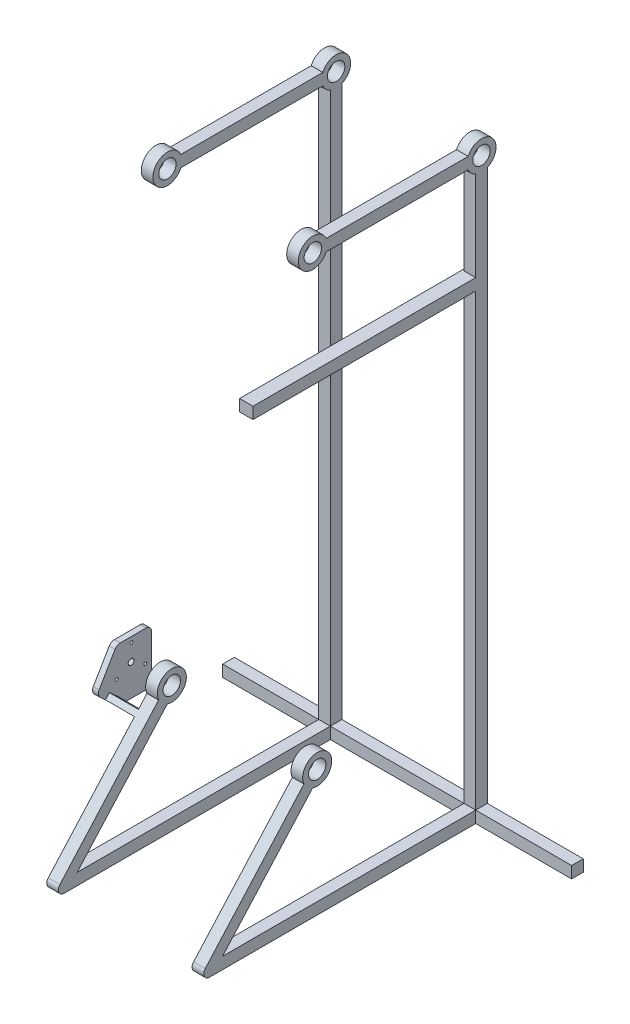
SolidWorks part; units mm, degrees
ref_plane "Front Plane" through (0, 0, 0) normal (0, 0, 1) x (1, 0, 0)
ref_plane "Top Plane" through (0, 0, 0) normal (0, 1, 0) x (1, 0, 0)
ref_plane "Right Plane" through (0, 0, 0) normal (1, 0, 0) x (0, 0, -1)
sketch "Sketch1" plane through (0, 0, 0) normal (1, 0, 0) x (0, 0, -1)
  line L0 (-277.0871, 516.4564) -> (-32.9129, 516.4564)
  line L1 (0, 483.5436) -> (0, -483.5436)
  line L2 (0, -483.5436) -> (-500, -483.5436)
  line L3 (-500, -483.5436) -> (-315.2753, -277.015)
  line L4 (-277.0871, 496.4564) -> (-32.9129, 496.4564)
  line L5 (-20, 483.5436) -> (-20, -463.5436)
  line L6 (-20, -463.5436) -> (-455.2786, -463.5436)
  line L7 (-455.2786, -463.5436) -> (-300.3681, -290.3483)
  line L8 (-300, -259.9368) -> (-285.0929, -273.2701) construction
  line L9 (-20, 496.4564) -> (0, 516.4564) construction
  line L10 (-300, 516.4564) -> (-300, 496.4564) construction
  line L11 (-300, 516.4564) -> (0, 516.4564) construction
  line L12 (-300, 496.4564) -> (-20, 496.4564) construction
  line L13 (-20, 496.4564) -> (-20, -463.5436) construction
  line L14 (0, 516.4564) -> (0, -483.5436) construction
  line L15 (-455.2786, -463.5436) -> (-285.0929, -273.2701) construction
  line L16 (-500, -483.5436) -> (-300, -259.9368) construction
  arc A0 (-32.9129, 496.4564) -> (-20, 483.5436) centre (-10, 506.4564) ccw
  arc A1 (-277.0871, 516.4564) -> (-277.0871, 496.4564) centre (-300, 506.4564) ccw
  arc A2 (-300.3681, -290.3483) -> (-315.2753, -277.015) centre (-292.5464, -266.6034) ccw
  circle A3 centre (-292.5464, -266.6034) radius 15
  circle A4 centre (-300, 506.4564) radius 15
  circle A5 centre (-10, 506.4564) radius 15
  arc A6 (0, 483.5436) -> (-32.9129, 516.4564) centre (-10, 506.4564) ccw
  point P17 (-300, 506.4564)
  point P18 (-292.5464, -266.6034)
  point P20 (-10, 506.4564)
  dimension "D6" = 50
  dimension "D7" = 30
  dimension "D8" = 30
  dimension "D9" = 30
  dimension "D1" = 1000
  dimension "D2" = 300
  dimension "D3" = 300
  dimension "D4" = 500
  dimension "D5" = 20
extrude "Boss-Extrude1" add sketch "Sketch1" along normal blind 20
fillet "Fillet1" radius 10 1 edges at (10, -483.5436, 500)
ref_plane "Plane1" through (-115, 0, 0) normal (1, 0, 0) x (0, 0, -1)
mirror "Mirror2" about plane through (-115, 0, 0) normal (1, 0, 0) of bodies 101
sketch "Sketch2" plane through (-115, 0, 0) normal (1, 0, 0) x (0, 0, -1)
  line L1 (-20, -463.5436) -> (0, -463.5436)
  line L2 (-20, -463.5436) -> (-20, -483.5436)
  line L3 (-20, -483.5436) -> (0, -483.5436)
  line L4 (0, -463.5436) -> (0, -483.5436)
extrude "Boss-Extrude2" add sketch "Sketch2" along normal blind 300 and the other way blind 300
sketch "Sketch3" plane through (20, 0, 0) normal (1, 0, 0) x (0, 0, -1)
  line L0 (0, -463.5436) -> (0, 483.5436) construction
  line L1 (0, 329.4564) -> (-403, 329.4564)
  line L2 (0, 329.4564) -> (0, 309.4564)
  line L3 (0, 309.4564) -> (-403, 309.4564)
  line L4 (-403, 329.4564) -> (-403, 309.4564)
  line L5 (-32.9129, 516.4564) -> (-277.0871, 516.4564) construction
  point P8 (0, 319.4564)
  dimension "D1" = 197
  dimension "D2" = 20
  dimension "D3" = 403
extrude "Boss-Extrude3" add sketch "Sketch3" against normal blind 23
sketch "Sketch4" plane through (-250, 0, 0) normal (-1, 0, 0) x (0, 0, 1)
  line L0 (330, -293.4778) -> (315.0929, -306.8111)
  line L1 (315.2753, -277.015) -> (485.0929, -466.8769) construction
  line L2 (455.2786, -463.5436) -> (300.3681, -290.3483) construction
  line L3 (315.0929, -306.8111) -> (321.7595, -314.2647)
  line L4 (321.7595, -314.2647) -> (336.6667, -300.9313)
  line L5 (336.6667, -300.9313) -> (330, -293.4778)
  dimension "D1" = 10
  dimension "D2" = 45
  dimension "D3" = 10
extrude "Boss-Extrude4" add sketch "Sketch4" along normal blind 50
sketch "Sketch5" plane through (-300, 0, 0) normal (-1, 0, 0) x (0, 0, 1)
  line L0 (317.153, -318.3849) -> (345.4801, -293.0483)
  line L1 (347.4434, -280.5426) -> (320.1257, -233.8792)
  line L2 (311.4957, -228.9313) -> (267.2291, -228.9313)
  line L3 (257.2291, -259.5016) -> (257.2291, -200.1335) construction
  line L4 (257.2291, -238.9313) -> (257.2291, -310.9313)
  line L5 (267.2291, -320.9313) -> (310.4863, -320.9313)
  line L6 (321.7595, -314.2647) -> (336.6667, -300.9313) construction
  line L7 (336.6667, -300.9313) -> (485.0929, -466.8769) construction
  line L8 (455.2786, -463.5436) -> (321.7595, -314.2647) construction
  arc A0 (320.1257, -233.8792) -> (311.4957, -228.9313) centre (311.4957, -238.9313) ccw
  arc A1 (345.4801, -293.0483) -> (347.4434, -280.5426) centre (338.8135, -285.5948) ccw
  arc A2 (317.153, -318.3849) -> (310.4863, -320.9313) centre (310.4863, -310.9313) cw
  arc A3 (257.2291, -310.9313) -> (267.2291, -320.9313) centre (267.2291, -310.9313) ccw
  arc A4 (267.2291, -228.9313) -> (257.2291, -238.9313) centre (267.2291, -238.9313) ccw
  circle A6 centre (317.5478, -280.2863) radius 2.5
  circle A7 centre (317.5478, -280.2863) radius 2.5
  circle A8 centre (268.1961, -281.4138) radius 2.5
  circle A9 centre (268.1961, -281.4138) radius 2.5
  circle A10 centre (291.8955, -238.1102) radius 2.5
  circle A11 centre (291.8955, -238.1102) radius 2.5
  circle A17 centre (292.5464, -266.6034) radius 5 construction
  circle A18 centre (292.5464, -266.6034) radius 5
  point P9 (351.1101, -288.0127)
  point P16 (317.2291, -228.9313)
  point P19 (351.5738, -287.598)
  point P22 (314.306, -320.9313)
  point P25 (257.2291, -320.9313)
  point P28 (257.2291, -228.9313)
  dimension "D5" = 10
  dimension "D1" = 20
  dimension "D2" = 10
  dimension "D3" = 60
  dimension "D4" = 92
  dimension "D6" = 0
  dimension "D7" = 0
  dimension "D8" = 0
extrude "Boss-Extrude5" add sketch "Sketch5" along normal blind 10
